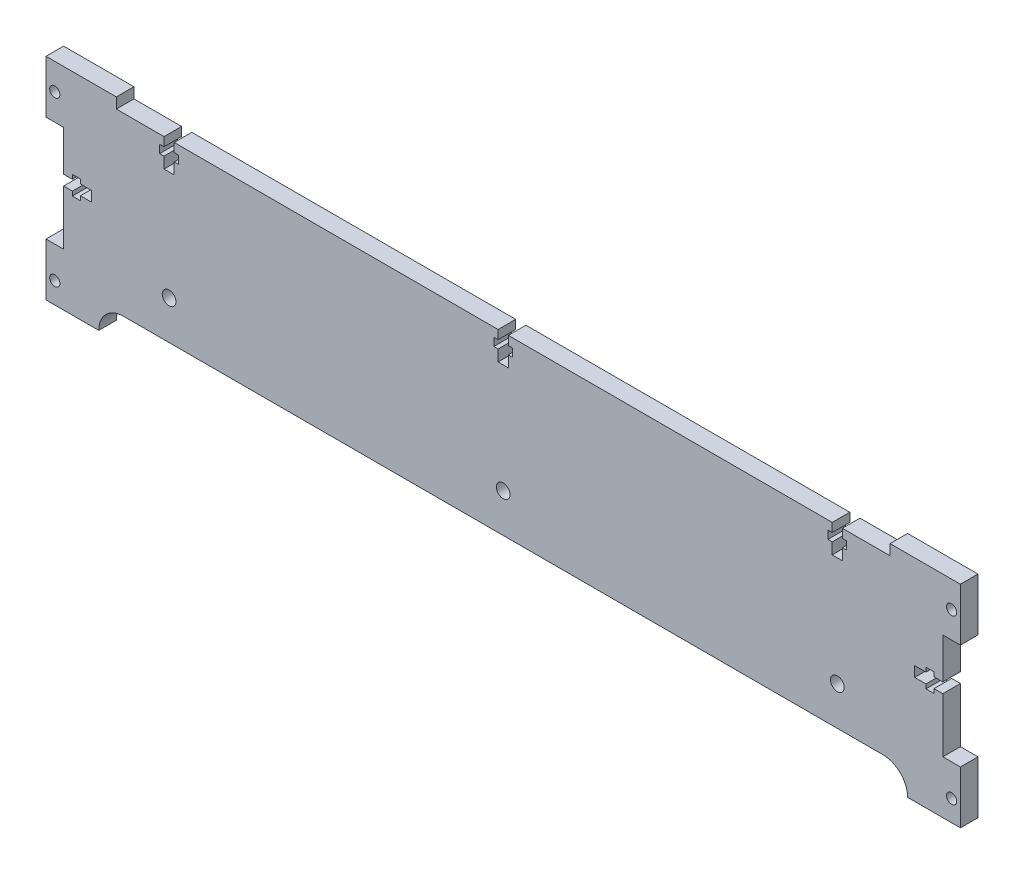
SolidWorks part; units mm, degrees
ref_plane "Front Plane" through (0, 0, 0) normal (0, 0, 1) x (1, 0, 0)
ref_plane "Top Plane" through (0, 0, 0) normal (0, 1, 0) x (1, 0, 0)
ref_plane "Right Plane" through (0, 0, 0) normal (1, 0, 0) x (0, 0, -1)
sketch "Sketch1" plane through (0, 0, 0) normal (0, 0, 1) x (1, 0, 0)
  line L73 (130, 6) -> (125, 6)
  line L74 (125, 6) -> (125, 21.55)
  line L75 (125, 36) -> (130, 36)
  line L76 (130, 36) -> (130, 51)
  line L77 (130, 51) -> (110, 51)
  line L78 (110, 51) -> (110, 48)
  line L79 (110, 48) -> (96.45, 48)
  line L80 (-110, 48) -> (-110, 51)
  line L81 (-110, 51) -> (-130, 51)
  line L82 (-130, 51) -> (-130, 36)
  line L83 (-130, 36) -> (-125, 36)
  line L84 (-125, 36) -> (-125, 24.45)
  line L85 (-125, 6) -> (-130, 6)
  line L86 (-130, 6) -> (-130, -9)
  line L87 (-130, -9) -> (-115, -9)
  line L88 (-108, -2) -> (108, -2)
  line L89 (115, -9) -> (130, -9)
  line L90 (130, -9) -> (130, 6)
  line L91 (130, 6) -> (125, 6)
  line L92 (125, 6) -> (125, 21.55)
  line L93 (125, 36) -> (130, 36)
  line L94 (130, 36) -> (130, 51)
  line L95 (130, 51) -> (110, 51)
  line L96 (110, 51) -> (110, 48)
  line L97 (110, 48) -> (96.45, 48)
  line L98 (-110, 48) -> (-110, 51)
  line L99 (-110, 51) -> (-130, 51)
  line L100 (-130, 51) -> (-130, 36)
  line L101 (-130, 36) -> (-125, 36)
  line L102 (-125, 36) -> (-125, 24.45)
  line L103 (-125, 6) -> (-130, 6)
  line L104 (-130, 6) -> (-130, -9)
  line L105 (-130, -9) -> (-115, -9)
  line L106 (-108, -2) -> (108, -2)
  line L107 (115, -9) -> (130, -9)
  line L108 (130, -9) -> (130, 6)
  line L247 (-1.45, 45.5) -> (-1.45, 48)
  line L248 (-1.45, 45.5) -> (-1.45, 48)
  line L249 (-1.45, 48) -> (-93.55, 48)
  line L250 (-1.45, 48) -> (-93.55, 48)
  line L251 (-93.55, 48) -> (-93.55, 45.5)
  line L252 (-93.55, 48) -> (-93.55, 45.5)
  line L253 (-93.55, 45.5) -> (-92.325, 45.5)
  line L254 (-93.55, 45.5) -> (-92.325, 45.5)
  line L255 (-92.325, 45.5) -> (-92.325, 43.2)
  line L256 (-92.325, 45.5) -> (-92.325, 43.2)
  line L257 (-92.325, 43.2) -> (-93.55, 43.2)
  line L258 (-92.325, 43.2) -> (-93.55, 43.2)
  line L259 (-93.55, 43.2) -> (-93.55, 40)
  line L260 (-93.55, 43.2) -> (-93.55, 40)
  line L261 (-93.55, 40) -> (-96.45, 40)
  line L262 (-93.55, 40) -> (-96.45, 40)
  line L263 (-96.45, 40) -> (-96.45, 43.2)
  line L264 (-96.45, 40) -> (-96.45, 43.2)
  line L265 (-96.45, 43.2) -> (-97.675, 43.2)
  line L266 (-96.45, 43.2) -> (-97.675, 43.2)
  line L267 (-97.675, 43.2) -> (-97.675, 45.5)
  line L268 (-97.675, 43.2) -> (-97.675, 45.5)
  line L269 (-97.675, 45.5) -> (-96.45, 45.5)
  line L270 (-97.675, 45.5) -> (-96.45, 45.5)
  line L271 (-96.45, 45.5) -> (-96.45, 48)
  line L272 (-96.45, 45.5) -> (-96.45, 48)
  line L273 (-96.45, 48) -> (-110, 48)
  line L274 (-96.45, 48) -> (-110, 48)
  line L275 (-125, 24.45) -> (-122.5, 24.45)
  line L276 (-125, 24.45) -> (-122.5, 24.45)
  line L277 (-122.5, 24.45) -> (-122.5, 25.675)
  line L278 (-122.5, 24.45) -> (-122.5, 25.675)
  line L279 (-122.5, 25.675) -> (-120.2, 25.675)
  line L280 (-122.5, 25.675) -> (-120.2, 25.675)
  line L281 (-120.2, 25.675) -> (-120.2, 24.45)
  line L282 (-120.2, 25.675) -> (-120.2, 24.45)
  line L283 (-120.2, 24.45) -> (-117, 24.45)
  line L284 (-120.2, 24.45) -> (-117, 24.45)
  line L285 (-117, 24.45) -> (-117, 21.55)
  line L286 (-117, 24.45) -> (-117, 21.55)
  line L287 (-117, 21.55) -> (-120.2, 21.55)
  line L288 (-117, 21.55) -> (-120.2, 21.55)
  line L289 (-120.2, 21.55) -> (-120.2, 20.325)
  line L290 (-120.2, 21.55) -> (-120.2, 20.325)
  line L291 (-120.2, 20.325) -> (-122.5, 20.325)
  line L292 (-120.2, 20.325) -> (-122.5, 20.325)
  line L293 (-122.5, 20.325) -> (-122.5, 21.55)
  line L294 (-122.5, 20.325) -> (-122.5, 21.55)
  line L295 (-122.5, 21.55) -> (-125, 21.55)
  line L296 (-122.5, 21.55) -> (-125, 21.55)
  line L297 (-125, 21.55) -> (-125, 6)
  line L298 (-125, 21.55) -> (-125, 6)
  line L299 (125, 21.55) -> (122.5, 21.55)
  line L300 (125, 21.55) -> (122.5, 21.55)
  line L301 (122.5, 21.55) -> (122.5, 20.325)
  line L302 (122.5, 21.55) -> (122.5, 20.325)
  line L303 (122.5, 20.325) -> (120.2, 20.325)
  line L304 (122.5, 20.325) -> (120.2, 20.325)
  line L305 (120.2, 20.325) -> (120.2, 21.55)
  line L306 (120.2, 20.325) -> (120.2, 21.55)
  line L307 (120.2, 21.55) -> (117, 21.55)
  line L308 (120.2, 21.55) -> (117, 21.55)
  line L309 (117, 21.55) -> (117, 24.45)
  line L310 (117, 21.55) -> (117, 24.45)
  line L311 (117, 24.45) -> (120.2, 24.45)
  line L312 (117, 24.45) -> (120.2, 24.45)
  line L313 (120.2, 24.45) -> (120.2, 25.675)
  line L314 (120.2, 24.45) -> (120.2, 25.675)
  line L315 (120.2, 25.675) -> (122.5, 25.675)
  line L316 (120.2, 25.675) -> (122.5, 25.675)
  line L317 (122.5, 25.675) -> (122.5, 24.45)
  line L318 (122.5, 25.675) -> (122.5, 24.45)
  line L319 (122.5, 24.45) -> (125, 24.45)
  line L320 (122.5, 24.45) -> (125, 24.45)
  line L321 (125, 24.45) -> (125, 36)
  line L322 (125, 24.45) -> (125, 36)
  line L323 (96.45, 48) -> (96.45, 45.5)
  line L324 (96.45, 48) -> (96.45, 45.5)
  line L325 (96.45, 45.5) -> (97.675, 45.5)
  line L326 (96.45, 45.5) -> (97.675, 45.5)
  line L327 (97.675, 45.5) -> (97.675, 43.2)
  line L328 (97.675, 45.5) -> (97.675, 43.2)
  line L329 (97.675, 43.2) -> (96.45, 43.2)
  line L330 (97.675, 43.2) -> (96.45, 43.2)
  line L331 (96.45, 43.2) -> (96.45, 40)
  line L332 (96.45, 43.2) -> (96.45, 40)
  line L333 (96.45, 40) -> (93.55, 40)
  line L334 (96.45, 40) -> (93.55, 40)
  line L335 (93.55, 40) -> (93.55, 43.2)
  line L336 (93.55, 40) -> (93.55, 43.2)
  line L337 (93.55, 43.2) -> (92.325, 43.2)
  line L338 (93.55, 43.2) -> (92.325, 43.2)
  line L339 (92.325, 43.2) -> (92.325, 45.5)
  line L340 (92.325, 43.2) -> (92.325, 45.5)
  line L341 (92.325, 45.5) -> (93.55, 45.5)
  line L342 (92.325, 45.5) -> (93.55, 45.5)
  line L343 (93.55, 45.5) -> (93.55, 48)
  line L344 (93.55, 45.5) -> (93.55, 48)
  line L345 (93.55, 48) -> (1.45, 48)
  line L346 (93.55, 48) -> (1.45, 48)
  line L347 (1.45, 48) -> (1.45, 45.5)
  line L348 (1.45, 48) -> (1.45, 45.5)
  line L349 (1.45, 45.5) -> (2.675, 45.5)
  line L350 (1.45, 45.5) -> (2.675, 45.5)
  line L351 (2.675, 45.5) -> (2.675, 43.2)
  line L352 (2.675, 45.5) -> (2.675, 43.2)
  line L353 (2.675, 43.2) -> (1.45, 43.2)
  line L354 (2.675, 43.2) -> (1.45, 43.2)
  line L355 (1.45, 43.2) -> (1.45, 40)
  line L356 (1.45, 43.2) -> (1.45, 40)
  line L357 (1.45, 40) -> (-1.45, 40)
  line L358 (1.45, 40) -> (-1.45, 40)
  line L359 (-1.45, 40) -> (-1.45, 43.2)
  line L360 (-1.45, 40) -> (-1.45, 43.2)
  line L361 (-1.45, 43.2) -> (-2.675, 43.2)
  line L362 (-1.45, 43.2) -> (-2.675, 43.2)
  line L363 (-2.675, 43.2) -> (-2.675, 45.5)
  line L364 (-2.675, 43.2) -> (-2.675, 45.5)
  line L365 (-2.675, 45.5) -> (-1.45, 45.5)
  line L366 (-2.675, 45.5) -> (-1.45, 45.5)
  arc A8 (-108, -2) -> (-115, -9) centre (-108, -9) ccw
  arc A9 (115, -9) -> (108, -2) centre (108, -9) ccw
  arc A10 (-108, -2) -> (-115, -9) centre (-108, -9) ccw
  arc A11 (115, -9) -> (108, -2) centre (108, -9) ccw
  dimension "D1" = 0
extrude "Boss-Extrude1" add sketch "Sketch1" along normal blind 5
sketch "Sketch2" plane through (0, 0, 5) normal (0, 0, 1) x (1, 0, 0)
  line L0 (93.55, 51) -> (93.55, 48) construction
  line L1 (96.45, 48) -> (96.45, 51) construction
  line L3 (-1.45, 51) -> (-1.45, 48) construction
  line L4 (-96.45, 51) -> (-96.45, 48) construction
  line L5 (-93.55, 48) -> (-93.55, 51) construction
  line L6 (93.55, 51) -> (93.55, 48) construction
  line L7 (96.45, 48) -> (96.45, 51) construction
  line L8 (1.45, 48) -> (1.45, 40)
  line L9 (-1.45, 51) -> (-1.45, 48) construction
  line L10 (-96.45, 51) -> (-96.45, 48) construction
  line L11 (-93.55, 48) -> (-93.55, 51) construction
  line L12 (-96.45, 51) -> (-93.55, 51) construction
  line L13 (-95, 51) -> (-95, 37.8578) construction
  line L14 (-1.45, 51) -> (1.45, 51) construction
  line L15 (0, 51) -> (0, 37.8578) construction
  line L16 (-127.5, 36) -> (-127.5, -14.1715) construction
  line L17 (-125, 36) -> (-130, 36) construction
  line L18 (-127.5, 36) -> (-127.5, 59.8791) construction
  line L19 (-125, 6) -> (-130, 6) construction
  line L20 (110, 48) -> (96.45, 48) construction
  line L21 (-96.45, 48) -> (-93.55, 48)
  line L22 (-96.45, 48) -> (-96.45, 40)
  line L23 (-96.45, 40) -> (-93.55, 40)
  line L24 (-93.55, 48) -> (-93.55, 40)
  line L25 (-97.675, 45.5) -> (-92.325, 45.5)
  line L26 (-97.675, 45.5) -> (-97.675, 43.2)
  line L27 (-97.675, 43.2) -> (-92.325, 43.2)
  line L28 (-92.325, 45.5) -> (-92.325, 43.2)
  line L29 (96.45, 51) -> (93.55, 51) construction
  line L30 (93.55, 48) -> (93.55, 51) construction
  line L31 (96.45, 51) -> (96.45, 48) construction
  line L32 (92.325, 45.5) -> (92.325, 43.2)
  line L33 (97.675, 43.2) -> (92.325, 43.2)
  line L34 (97.675, 45.5) -> (97.675, 43.2)
  line L35 (97.675, 45.5) -> (92.325, 45.5)
  line L36 (93.55, 48) -> (93.55, 40)
  line L37 (96.45, 40) -> (93.55, 40)
  line L38 (96.45, 48) -> (96.45, 40)
  line L39 (96.45, 48) -> (93.55, 48)
  line L40 (1.45, 48) -> (1.45, 51) construction
  line L41 (-1.45, 48) -> (1.45, 48)
  line L42 (-1.45, 48) -> (-1.45, 40)
  line L43 (-1.45, 40) -> (1.45, 40)
  line L45 (-93.55, 40) -> (-1.45, 40) construction
  line L46 (-92.325, 45.5) -> (-2.675, 45.5) construction
  line L47 (-2.675, 43.2) -> (2.675, 43.2)
  line L48 (-2.675, 43.2) -> (-2.675, 45.5)
  line L49 (-2.675, 45.5) -> (2.675, 45.5)
  line L50 (2.675, 43.2) -> (2.675, 45.5)
  line L51 (-2.675, 43.2) -> (-92.325, 43.2) construction
  line L52 (-125, 23) -> (-114.5889, 23) construction
  line L53 (-125, 6) -> (-125, 36) construction
  line L54 (125, 23) -> (114.5889, 23) construction
  line L55 (-125, 24.45) -> (-117, 24.45)
  line L56 (-125, 24.45) -> (-125, 21.55)
  line L57 (-125, 21.55) -> (-117, 21.55)
  line L58 (-117, 24.45) -> (-117, 21.55)
  line L59 (-122.5, 20.325) -> (-120.2, 20.325)
  line L60 (-122.5, 20.325) -> (-122.5, 25.675)
  line L61 (-122.5, 25.675) -> (-120.2, 25.675)
  line L62 (-120.2, 20.325) -> (-120.2, 25.675)
  line L63 (120.2, 20.325) -> (120.2, 25.675)
  line L64 (122.5, 25.675) -> (120.2, 25.675)
  line L65 (122.5, 20.325) -> (122.5, 25.675)
  line L66 (122.5, 20.325) -> (120.2, 20.325)
  line L67 (117, 24.45) -> (117, 21.55)
  line L68 (125, 21.55) -> (117, 21.55)
  line L69 (125, 24.45) -> (125, 21.55)
  line L70 (125, 24.45) -> (117, 24.45)
  circle A0 centre (-127.5, 43.5) radius 1.45
  circle A1 centre (-127.5, -3) radius 1.45
  circle A2 centre (127.5, -3) radius 1.45
  circle A3 centre (127.5, 43.5) radius 1.45
  point P4 (0, 45.5)
  point P35 (-95, 45.5)
  point P62 (-125, 23)
  point P63 (-122.5, 23)
  dimension "D1" = 2.9
  dimension "D3" = 9
  dimension "D2" = 7.5
  dimension "D4" = 8
  dimension "D5" = 2.3
  dimension "D6" = 5.35
  dimension "D7" = 2.5
  dimension "D8" = 13
  dimension "D9" = 8
  dimension "D10" = 2.9
  dimension "D11" = 2.5
extrude "Cut-Extrude1" cut sketch "Sketch2" against normal through all
sketch "Sketch3" plane through (0, 0, 5) normal (0, 0, 1) x (1, 0, 0)
  line L0 (-125, 18) -> (-125, 0) construction
  line L1 (-125, 18) -> (-125, 0) construction
  line L2 (-125, 9) -> (137.7275, 9) construction
  line L3 (0, 0) -> (0, 92.3106) construction
  line L4 (125, 36) -> (125, 6) construction
  circle A0 centre (0, 9) radius 1.95
  circle A1 centre (-95, 9) radius 1.95
  circle A2 centre (95, 9) radius 1.95
  dimension "D1" = 3.9
  dimension "D2" = 30
  dimension "D3" = 30
extrude "Cut-Extrude2" cut sketch "Sketch3" against normal through all
